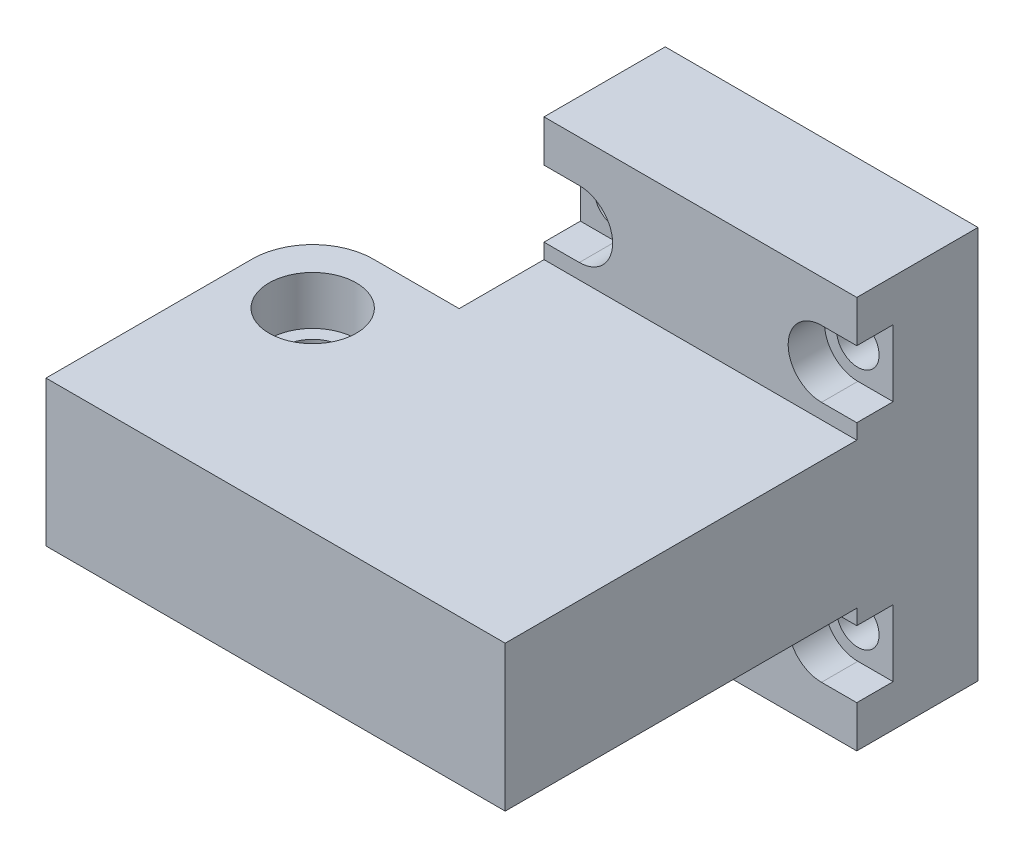
SolidWorks part; units mm, degrees
ref_plane "Plan de face" through (0, 0, 0) normal (0, 0, 1) x (1, 0, 0)
ref_plane "Plan de dessus" through (0, 0, 0) normal (0, 1, 0) x (1, 0, 0)
ref_plane "Plan de droite" through (0, 0, 0) normal (1, 0, 0) x (0, 0, -1)
sketch "Esquisse1" plane through (0, 0, 0) normal (0, 0, 1) x (1, 0, 0)
  line L1 (-10.8193, 11.9786) -> (14.9807, 11.9786)
  line L2 (-10.8193, 11.9786) -> (-10.8193, -20.4214)
  line L3 (-10.8193, -20.4214) -> (14.9807, -20.4214)
  line L4 (14.9807, 11.9786) -> (14.9807, -20.4214)
  dimension "D1" = 25.8
  dimension "D2" = 32.4
extrude "Boss.-Extru.1" add sketch "Esquisse1" along normal blind 10
sketch "Esquisse2" plane through (0, 0, 10) normal (0, 0, 1) x (1, 0, 0)
  line L0 (-10.8193, 11.9786) -> (-10.8193, -20.4214) construction
  line L1 (-10.8193, 1.7786) -> (14.9807, 1.7786)
  line L2 (-10.8193, 1.7786) -> (-10.8193, -10.2214)
  line L3 (-10.8193, -10.2214) -> (14.9807, -10.2214)
  line L4 (14.9807, 1.7786) -> (14.9807, -10.2214)
  line L5 (14.9807, -20.4214) -> (14.9807, 11.9786) construction
  point P8 (14.9807, -4.2214)
  dimension "D1" = 12
extrude "Boss.-Extru.2" add sketch "Esquisse2" along normal blind 29
sketch "Esquisse3" plane through (0, 0, 10) normal (0, 0, 1) x (1, 0, 0)
  line L0 (14.9807, -20.4214) -> (14.9807, -10.2214) construction
  line L1 (-7.9093, 5.7786) -> (12.0707, 5.7786) construction
  line L2 (-7.9093, 5.7786) -> (-7.9093, -14.2214) construction
  line L3 (-7.9093, -14.2214) -> (12.0707, -14.2214) construction
  line L4 (12.0707, 5.7786) -> (12.0707, -14.2214) construction
  line L5 (-10.8193, -20.4214) -> (14.9807, -20.4214) construction
  line L6 (14.9807, 11.9786) -> (-10.8193, 11.9786) construction
  line L7 (-10.8193, 11.9786) -> (-10.8193, 1.7786) construction
  circle A0 centre (12.0707, 5.7786) radius 2.75
  circle A1 centre (-7.9093, 5.7786) radius 2.75
  circle A2 centre (-7.9093, -14.2214) radius 2.75
  circle A3 centre (12.0707, -14.2214) radius 2.75
  dimension "D5" = 5.5
  dimension "D1" = 2.91
  dimension "D2" = 6.2
  dimension "D3" = 6.2
  dimension "D4" = 2.91
extrude "Enlèv. mat.-Extru.1" cut sketch "Esquisse3" against normal blind 3
sketch "Esquisse4" plane through (0, 0, 7) normal (0, 0, 1) x (1, 0, 0)
  circle A0 centre (12.0707, 5.7786) radius 1.75
  circle A1 centre (-7.9093, 5.7786) radius 1.75
  circle A2 centre (12.0707, -14.2214) radius 1.75
  circle A3 centre (-7.9093, -14.2214) radius 1.75
  dimension "D1" = 3.5
extrude "Enlèv. mat.-Extru.2" cut sketch "Esquisse4" against normal up to vertex (7 mm away)
sketch "Esquisse5" plane through (-10.8193, 0, 0) normal (-1, 0, 0) x (0, 0, 1)
  line L0 (39, 1.7786) -> (10, 1.7786) construction
  line L1 (39, -10.2214) -> (17, -10.2214)
  line L2 (39, -10.2214) -> (39, 1.7786)
  line L3 (39, 1.7786) -> (17, 1.7786)
  line L4 (17, -10.2214) -> (17, 1.7786)
  dimension "D1" = 22
extrude "Boss.-Extru.3" add sketch "Esquisse5" along normal blind 12.08
fillet "Congé1" radius 5 1 edges at (-22.8993, -4.2214, 17)
sketch "Esquisse6" plane through (0, -10.2214, 0) normal (0, -1, 0) x (1, 0, 0)
  line L0 (-22.8993, 22) -> (-22.8993, 39) construction
  line L1 (-17.8993, 17) -> (-10.8193, 17) construction
  circle A0 centre (-16.8993, 23) radius 2.5
  dimension "D3" = 5
  dimension "D1" = 6
  dimension "D2" = 6
extrude "Enlèv. mat.-Extru.3" cut sketch "Esquisse6" against normal up to vertex
sketch "Esquisse7" plane through (0, 1.7786, 0) normal (0, 1, 0) x (1, 0, 0)
  circle A0 centre (-16.8993, -23) radius 3.6
  dimension "D1" = 7.2
extrude "Enlèv. mat.-Extru.4" cut sketch "Esquisse7" against normal blind 4
sketch "Esquisse8" plane through (0, 0, 10) normal (0, 0, 1) x (1, 0, 0)
  line L0 (12.0707, -11.4714) -> (14.9807, -11.4714)
  line L1 (14.9807, -20.4214) -> (14.9807, -10.2214) construction
  line L2 (14.9807, -11.4714) -> (14.9807, -16.9714)
  line L3 (14.9807, -16.9714) -> (12.0707, -16.9714)
  line L4 (12.0707, -16.9714) -> (12.0707, -11.4714)
  line L5 (14.9807, 1.7786) -> (14.9807, 11.9786) construction
  line L6 (12.0707, 3.0286) -> (14.9807, 3.0286)
  line L7 (12.0707, 3.0286) -> (12.0707, 8.5286)
  line L8 (12.0707, 8.5286) -> (14.9807, 8.5286)
  line L9 (14.9807, 3.0286) -> (14.9807, 8.5286)
  line L10 (-10.8193, 11.9786) -> (-10.8193, 1.7786) construction
  line L11 (-7.9093, 3.0286) -> (-10.8193, 3.0286)
  line L12 (-7.9093, 3.0286) -> (-7.9093, 8.5286)
  line L13 (-7.9093, 8.5286) -> (-10.8193, 8.5286)
  line L14 (-10.8193, 3.0286) -> (-10.8193, 8.5286)
  line L15 (-10.8193, -10.2214) -> (-10.8193, -20.4214) construction
  line L16 (-7.9093, -11.4714) -> (-10.8193, -11.4714)
  line L17 (-7.9093, -11.4714) -> (-7.9093, -16.9714)
  line L18 (-7.9093, -16.9714) -> (-10.8193, -16.9714)
  line L19 (-10.8193, -11.4714) -> (-10.8193, -16.9714)
  circle A0 centre (12.0707, -14.2214) radius 2.75 construction
  circle A1 centre (12.0707, 5.7786) radius 2.75 construction
  circle A2 centre (-7.9093, 5.7786) radius 2.75 construction
  circle A3 centre (-7.9093, -14.2214) radius 2.75 construction
extrude "Enlèv. mat.-Extru.5" cut sketch "Esquisse8" against normal blind 3
equation "\"D3@Esquisse3\"=\"D2@Esquisse3\""
equation "\"D4@Esquisse3\"=\"D1@Esquisse3\""
equation "\"D2@Esquisse6\"=\"D1@Esquisse6\""
